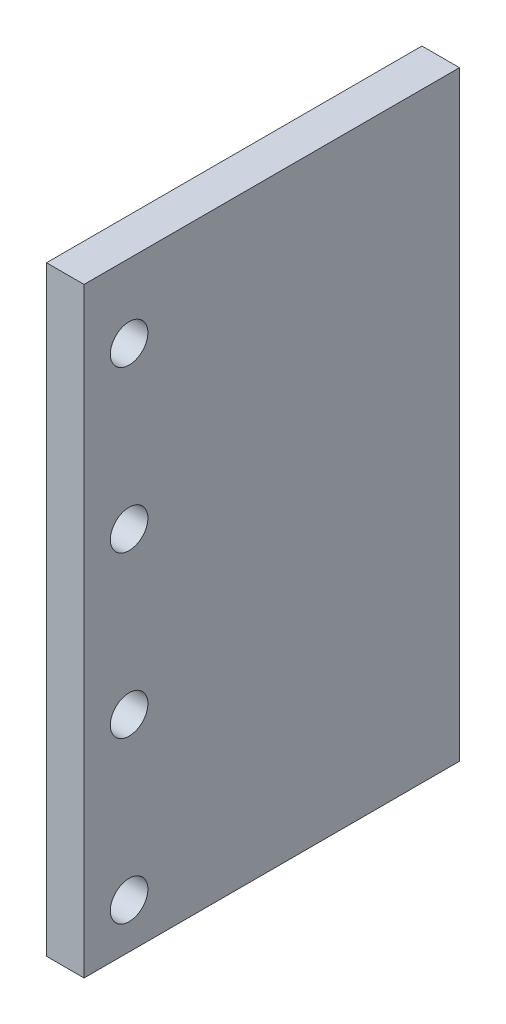
SolidWorks part; units mm, degrees
ref_plane "Ön Düzlem" through (0, 0, 0) normal (1, 0, 0) x (0, 1, 0)
ref_plane "Üst Düzlem" through (0, 0, 0) normal (0, 0, 1) x (0, 1, 0)
ref_plane "Sağ Düzlem" through (0, 0, 0) normal (0, 1, 0) x (-1, 0, 0)
sketch "Çizim1" plane through (0, 0, 0) normal (1, 0, 0) x (0, 1, 0)
  line L1 (0, 0) -> (40, 0)
  line L2 (0, 0) -> (0, 25)
  line L3 (0, 25) -> (40, 25)
  line L4 (40, 0) -> (40, 25)
  circle A0 centre (3, 22) radius 1.25
  circle A1 centre (13.7, 22) radius 1.25
  circle A2 centre (24.4, 22) radius 1.25
  circle A3 centre (35.1, 22) radius 1.25
  dimension "D3" = 2.5
  dimension "D1" = 40
  dimension "D2" = 25
  dimension "D4" = 3
  dimension "D5" = 3
  dimension "D6" = 4
extrude "Yükseklik-Ekstrüzyon1" add sketch "Çizim1" along normal blind 2.5
